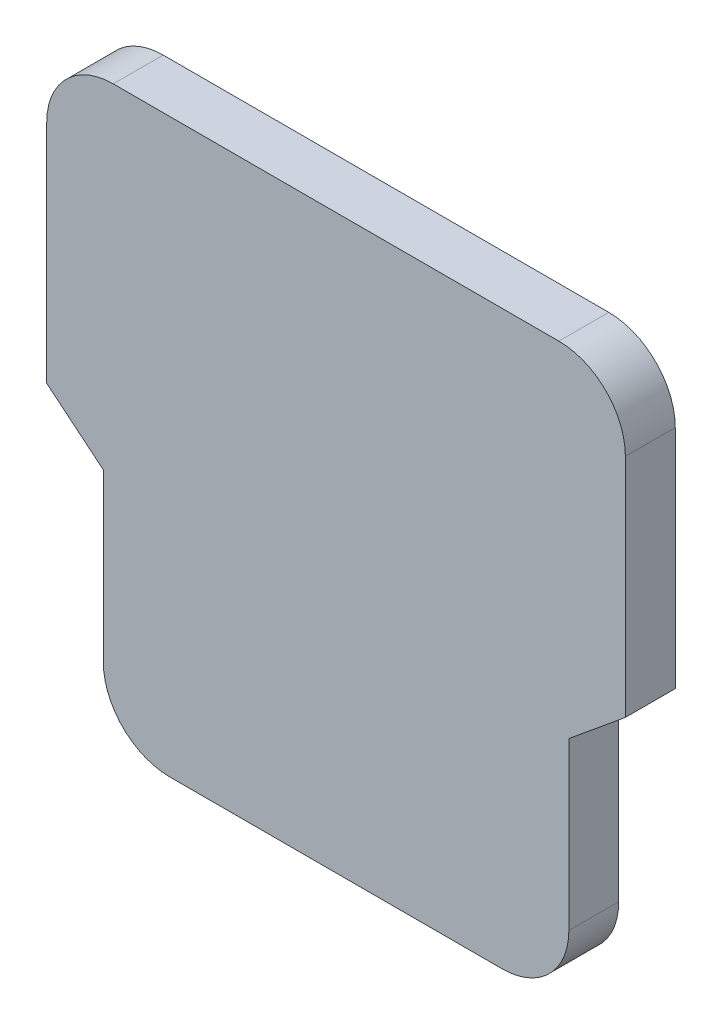
SolidWorks part; units mm, degrees
ref_plane "Płaszczyzna przednia" through (0, 0, 0) normal (0, 0, 1) x (1, 0, 0)
ref_plane "Płaszczyzna górna" through (0, 0, 0) normal (0, 1, 0) x (1, 0, 0)
ref_plane "Płaszczyzna prawa" through (0, 0, 0) normal (1, 0, 0) x (0, 0, -1)
sketch "Szkic1" plane through (0, 0, 0) normal (0, 0, 1) x (1, 0, 0)
  line L0 (-16.3959, 3.9924) -> (32.3312, 3.9924) construction
  line L1 (-10.1546, 12.7924) -> (7.2454, 12.7924)
  line L2 (-10.1546, 12.7924) -> (-10.1546, 3.9924)
  line L3 (-8.4546, -4.4076) -> (5.5454, -4.4076)
  line L4 (7.2454, 12.7924) -> (7.2454, 3.9924)
  line L6 (-8.4546, -4.4076) -> (-8.4546, 2.5924)
  line L7 (-1.4546, -4.4076) -> (-1.4546, 12.7924) construction
  line L8 (-8.4546, 2.5924) -> (-10.1546, 3.9924)
  line L9 (5.5454, -4.4076) -> (5.5454, 2.5924)
  line L10 (5.5454, 2.5924) -> (7.2454, 3.9924)
  line L11 (-8.4546, 2.5924) -> (7.2454, 2.5924) construction
  circle A0 centre (-1.4546, -4.4076) radius 7 construction
  dimension "D1" = 17.4
  dimension "D2" = 17.2
  dimension "D3" = 8.8
extrude "Dodanie-wyciągnięcie1" add sketch "Szkic1" along normal blind 1.5
fillet "Zaokrąglenie2" radius 2 4 edges at (7.2454, 12.7924, 0.75) (-10.1546, 12.7924, 0.75) (-8.4546, -4.4076, 0.75) (5.5454, -4.4076, 0.75)
ref_plane "Płaszczyzna1" through (-1.4546, 0, 0) normal (1, 0, 0) x (0, 0, -1)
